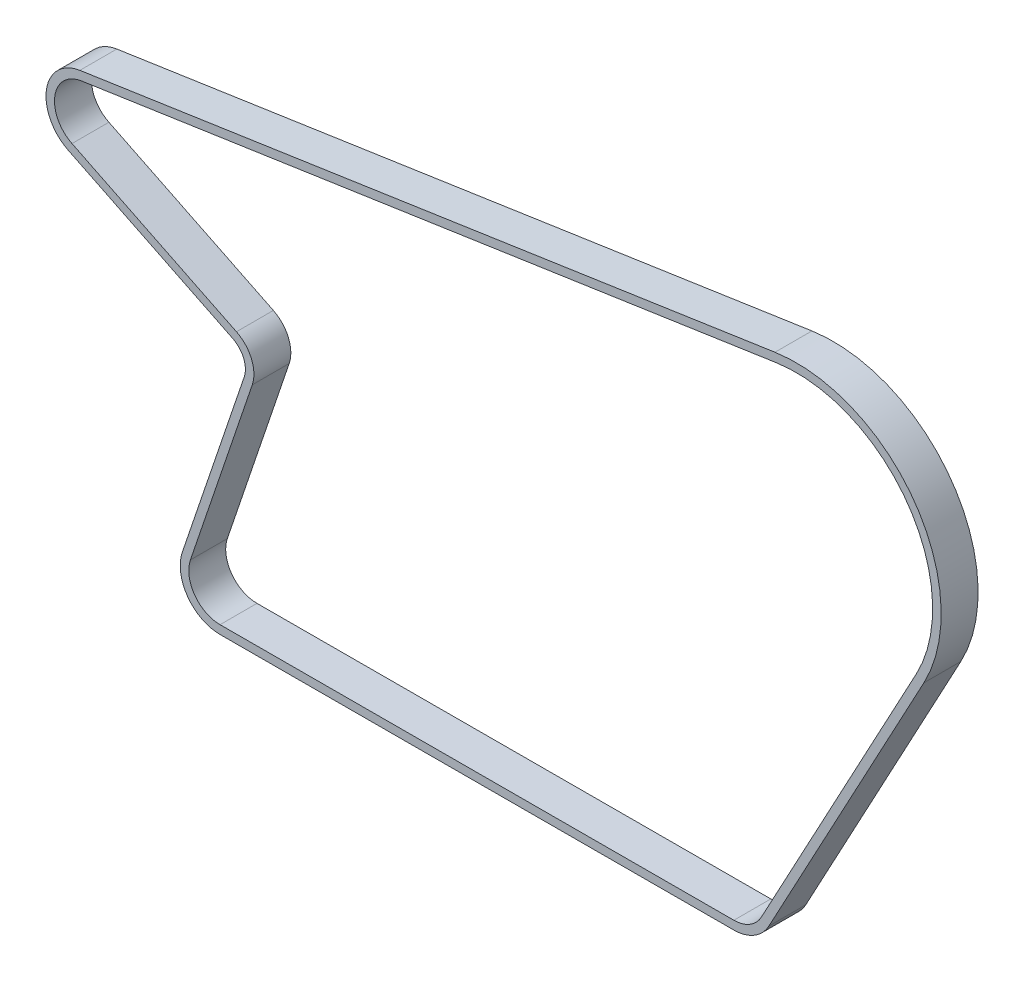
SolidWorks part; units mm, degrees
ref_plane "Front Plane" through (0, 0, 0) normal (0, 0, 1) x (1, 0, 0)
ref_plane "Top Plane" through (0, 0, 0) normal (0, 1, 0) x (1, 0, 0)
ref_plane "Right Plane" through (0, 0, 0) normal (1, 0, 0) x (0, 0, -1)
sketch "Sketch2" plane through (0, 0, 0) normal (0, 0, 1) x (1, 0, 0)
  line L0 (0, 0) -> (1, 0) construction
  line L1 (0, 0) -> (0, 1) construction
  line L2 (-4.8477, -9.8742) -> (53.0614, -38.3043)
  line L3 (58.632, -51.7084) -> (36.8538, -115.9845)
  line L6 (237.8921, -124.3895) -> (292.4758, -22.9175)
  line L7 (243.1393, 47.2988) -> (-1.6189, 10.8802)
  line L8 (47.2925, -130.5144) -> (228.2252, -130.1785)
  arc A0 (-1.6189, 10.8802) -> (-4.8477, -9.8742) centre (0, 0) ccw
  arc A1 (53.0614, -38.3043) -> (58.632, -51.7084) centre (48.2138, -48.1785) cw
  arc A2 (36.8538, -115.9845) -> (47.2925, -130.5144) centre (47.2721, -119.5145) ccw
  arc A4 (228.2252, -130.1785) -> (237.8921, -124.3895) centre (228.2048, -119.1785) ccw
  arc A5 (292.4758, -22.9175) -> (243.1393, 47.2988) centre (250.2037, -0.1785) ccw
extrude "Extrude-Thin1" add sketch "Sketch2" along normal blind 10 and the other way blind 3 thin
